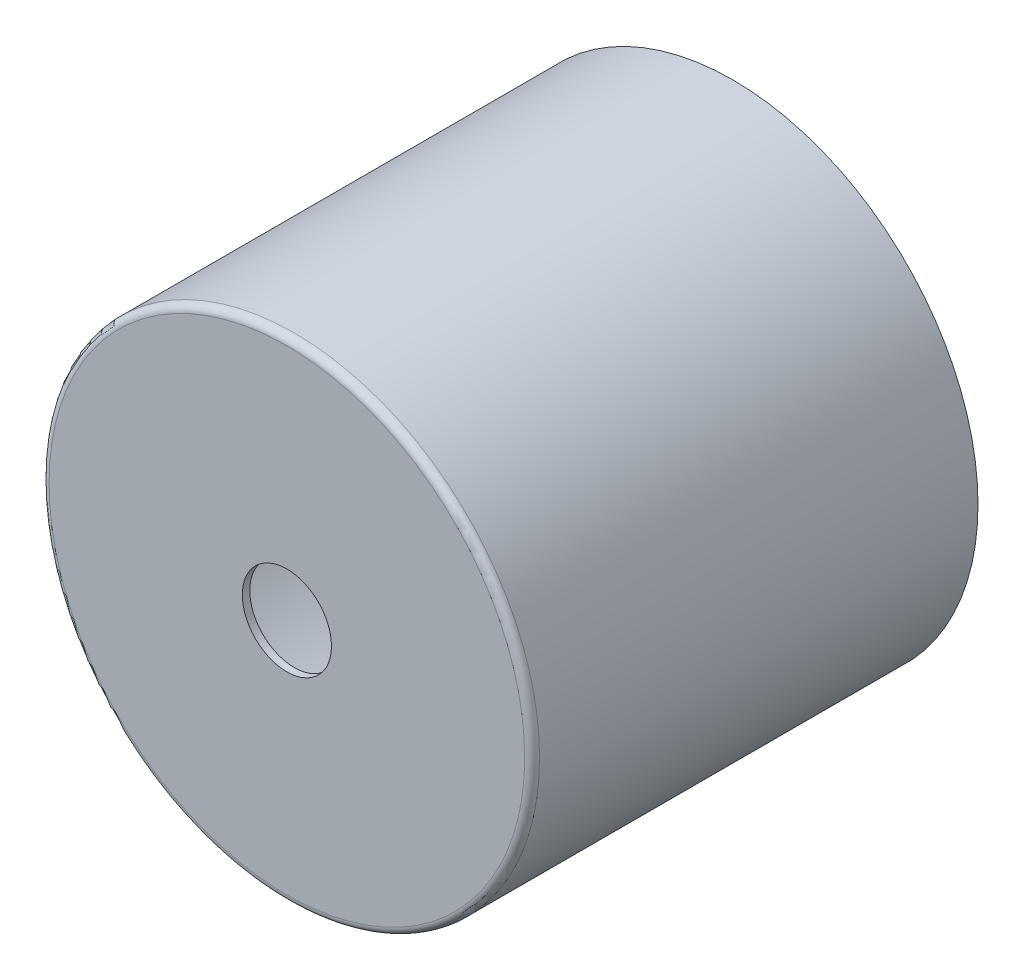
SolidWorks part; units mm, degrees
ref_plane "Front Plane" through (0, 0, 0) normal (0, 0, 1) x (1, 0, 0)
ref_plane "Top Plane" through (0, 0, 0) normal (0, 1, 0) x (1, 0, 0)
ref_plane "Right Plane" through (0, 0, 0) normal (1, 0, 0) x (0, 0, -1)
sketch "Sketch1" plane through (0, 0, 0) normal (0, 0, 1) x (1, 0, 0)
  circle A0 centre (0, 0) radius 16.5
  dimension "D1" = 33
extrude "Boss-Extrude1" add sketch "Sketch1" against normal blind 30
shell "Shell1" thickness 0.5
sketch "Sketch2" plane through (0, 0, 0) normal (0, 0, 1) x (1, 0, 0)
  circle A0 centre (0, 0) radius 3
  dimension "D1" = 6
extrude "Cut-Extrude1" cut sketch "Sketch2" against normal through all
fillet "Fillet1" radius 0.5 1 edges at (16.5, 0, 0)
